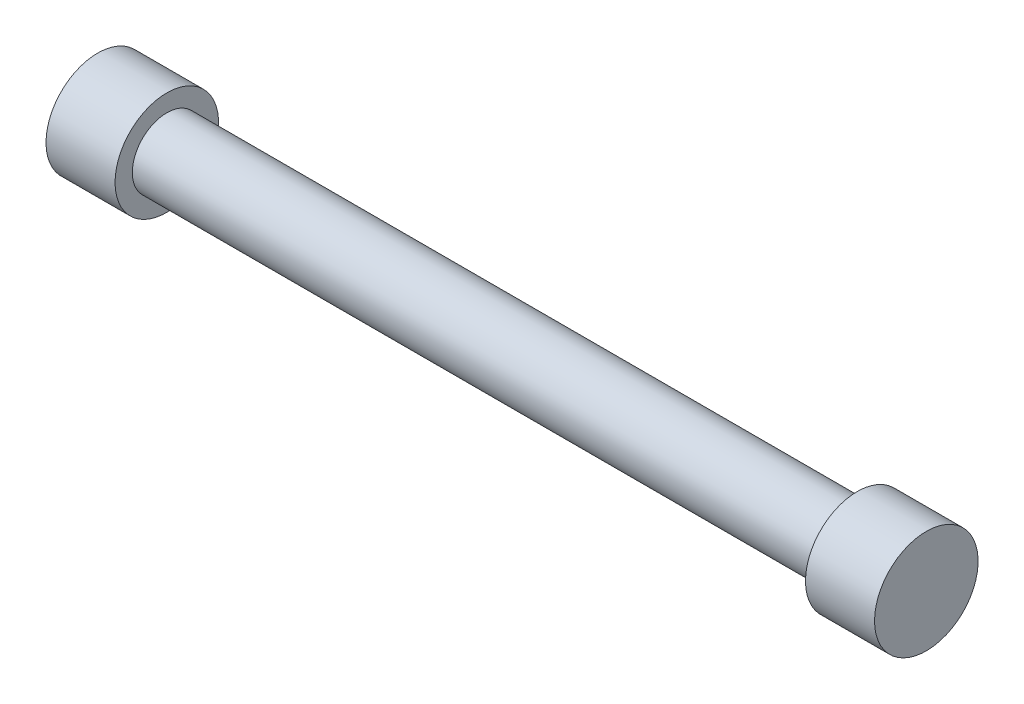
SolidWorks part; units mm, degrees
material "A286 Iron Base Superalloy"
ref_plane "Front Plane" through (0, 0, 0) normal (0, 0, 1) x (1, 0, 0)
ref_plane "Top Plane" through (0, 0, 0) normal (0, 1, 0) x (1, 0, 0)
ref_plane "Right Plane" through (0, 0, 0) normal (1, 0, 0) x (0, 0, -1)
sketch "Sketch1" plane through (0, 0, 0) normal (0, 1, 0) x (1, 0, 0)
  line L0 (0, 0) -> (0, -1.5)
  line L1 (0, -1.5) -> (2, -1.5)
  line L2 (2, -1.5) -> (2, -1)
  line L3 (2, -1) -> (22, -1)
  line L4 (22, -1) -> (22, -1.5)
  line L5 (22, -1.5) -> (24, -1.5)
  line L6 (24, -1.5) -> (24, 0)
  line L7 (0, 0) -> (24, 0) construction
  line L8 (0, 0) -> (24, 0)
  dimension "D1" = 1.5
  dimension "D2" = 1.5
  dimension "D3" = 1
  dimension "D4" = 2
  dimension "D5" = 2
  dimension "D6" = 20
  dimension "D7" = 24
revolve "Revolve1" add sketch "Sketch1" angle 360 about L8
